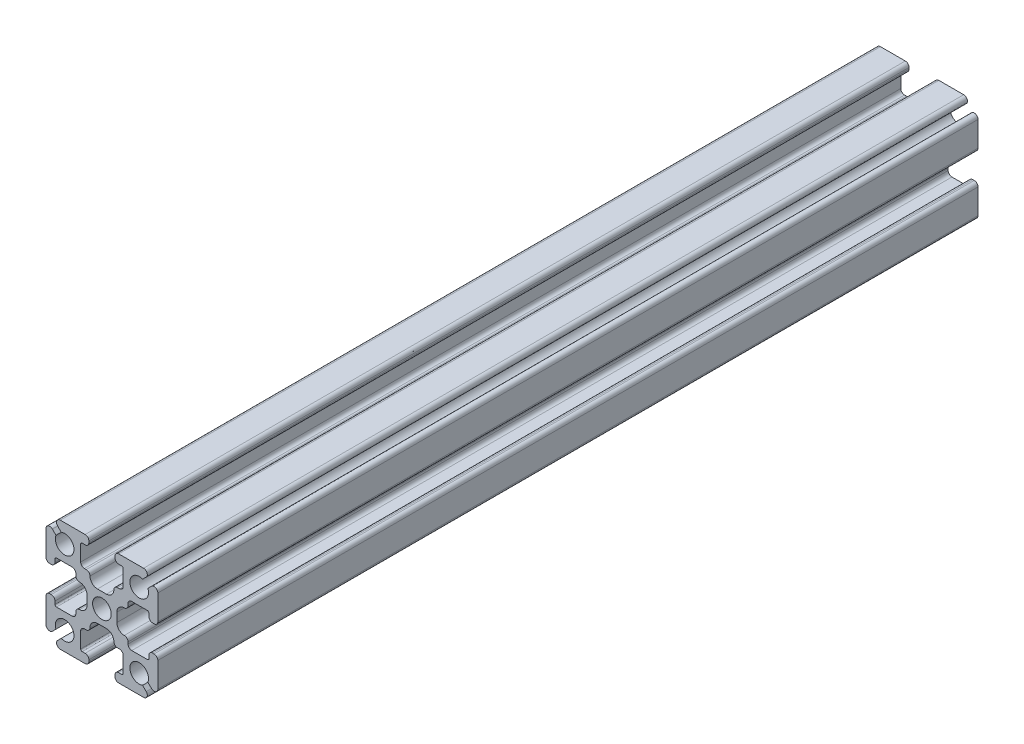
SolidWorks part; units mm, degrees
ref_plane "Front" through (0, 0, 0) normal (0, 0, 1) x (1, 0, 0)
ref_plane "Top" through (0, 0, 0) normal (0, 1, 0) x (1, 0, 0)
ref_plane "Right" through (0, 0, 0) normal (1, 0, 0) x (0, 0, -1)
sketch "Sketch1" plane through (0, 0, 0) normal (0, 0, 1) x (1, 0, 0)
  line L0 (6.6464, 5.9393) -> (6.1636, 5.4565)
  line L1 (5.4565, 6.1636) -> (5.9393, 6.6464)
  line L2 (5.5858, 7.5) -> (2.25, 7.5)
  line L3 (1.75, 7) -> (1.75, 6.8)
  line L4 (2.25, 6.3) -> (2.65, 6.3)
  line L5 (2.85, 6.1) -> (2.85, 4)
  line L6 (2.35, 3.5) -> (2.1, 3.5)
  line L7 (0.6, 2) -> (-0.6, 2)
  line L8 (-2.1, 3.5) -> (-2.35, 3.5)
  line L9 (-2.85, 4) -> (-2.85, 6.1)
  line L10 (-2.65, 6.3) -> (-2.25, 6.3)
  line L11 (-1.75, 6.8) -> (-1.75, 7)
  line L12 (-2.25, 7.5) -> (-5.5858, 7.5)
  line L13 (-5.9393, 6.6464) -> (-5.4565, 6.1636)
  line L14 (-6.1636, 5.4565) -> (-6.6464, 5.9393)
  line L15 (-7.5, 5.5858) -> (-7.5, 2.25)
  line L16 (-7, 1.75) -> (-6.8, 1.75)
  line L17 (-6.3, 2.25) -> (-6.3, 2.65)
  line L18 (-6.1, 2.85) -> (-4, 2.85)
  line L19 (-3.5, 2.35) -> (-3.5, 2.1)
  line L20 (-2, 0.6) -> (-2, -0.6)
  line L21 (-3.5, -2.1) -> (-3.5, -2.35)
  line L22 (-4, -2.85) -> (-6.1, -2.85)
  line L23 (-6.3, -2.65) -> (-6.3, -2.25)
  line L24 (-6.8, -1.75) -> (-7, -1.75)
  line L25 (-7.5, -2.25) -> (-7.5, -5.5858)
  line L26 (-6.6464, -5.9393) -> (-6.1636, -5.4565)
  line L27 (-5.4565, -6.1636) -> (-5.9393, -6.6464)
  line L28 (-5.5858, -7.5) -> (-2.25, -7.5)
  line L29 (-1.75, -7) -> (-1.75, -6.8)
  line L30 (-2.25, -6.3) -> (-2.65, -6.3)
  line L31 (-2.85, -6.1) -> (-2.85, -4)
  line L32 (-2.35, -3.5) -> (-2.1, -3.5)
  line L33 (-0.6, -2) -> (0.6, -2)
  line L34 (2.1, -3.5) -> (2.35, -3.5)
  line L35 (2.85, -4) -> (2.85, -6.1)
  line L36 (2.65, -6.3) -> (2.25, -6.3)
  line L37 (1.75, -6.8) -> (1.75, -7)
  line L38 (2.25, -7.5) -> (5.5858, -7.5)
  line L39 (5.9393, -6.6464) -> (5.4565, -6.1636)
  line L40 (6.1636, -5.4565) -> (6.6464, -5.9393)
  line L41 (7.5, -5.5858) -> (7.5, -2.25)
  line L42 (7, -1.75) -> (6.8, -1.75)
  line L43 (6.3, -2.25) -> (6.3, -2.65)
  line L44 (6.1, -2.85) -> (4, -2.85)
  line L45 (3.5, -2.35) -> (3.5, -2.1)
  line L46 (2, -0.6) -> (2, 0.6)
  line L47 (3.5, 2.1) -> (3.5, 2.35)
  line L48 (4, 2.85) -> (6.1, 2.85)
  line L49 (6.3, 2.65) -> (6.3, 2.25)
  line L50 (6.8, 1.75) -> (7, 1.75)
  line L51 (7.5, 2.25) -> (7.5, 5.5858)
  circle A0 centre (0, 0) radius 1.25
  arc A1 (6.1636, 5.4565) -> (5.4565, 6.1636) centre (5, 5) cw
  arc A2 (5.9393, 6.6464) -> (5.5858, 7.5) centre (5.5858, 7) ccw
  arc A3 (2.25, 7.5) -> (1.75, 7) centre (2.25, 7) ccw
  arc A4 (1.75, 6.8) -> (2.25, 6.3) centre (2.25, 6.8) ccw
  arc A5 (2.65, 6.3) -> (2.85, 6.1) centre (2.65, 6.1) cw
  arc A6 (2.85, 4) -> (2.35, 3.5) centre (2.35, 4) cw
  arc A7 (2.1, 3.5) -> (1.6, 3) centre (2.1, 3) ccw
  arc A8 (1.6, 3) -> (0.6, 2) centre (0.6, 3) cw
  arc A9 (-0.6, 2) -> (-1.6, 3) centre (-0.6, 3) cw
  arc A10 (-1.6, 3) -> (-2.1, 3.5) centre (-2.1, 3) ccw
  arc A11 (-2.35, 3.5) -> (-2.85, 4) centre (-2.35, 4) cw
  arc A12 (-2.85, 6.1) -> (-2.65, 6.3) centre (-2.65, 6.1) cw
  arc A13 (-2.25, 6.3) -> (-1.75, 6.8) centre (-2.25, 6.8) ccw
  arc A14 (-1.75, 7) -> (-2.25, 7.5) centre (-2.25, 7) ccw
  arc A15 (-5.5858, 7.5) -> (-5.9393, 6.6464) centre (-5.5858, 7) ccw
  arc A16 (-5.4565, 6.1636) -> (-6.1636, 5.4565) centre (-5, 5) cw
  arc A17 (-6.6464, 5.9393) -> (-7.5, 5.5858) centre (-7, 5.5858) ccw
  arc A18 (-7.5, 2.25) -> (-7, 1.75) centre (-7, 2.25) ccw
  arc A19 (-6.8, 1.75) -> (-6.3, 2.25) centre (-6.8, 2.25) ccw
  arc A20 (-6.3, 2.65) -> (-6.1, 2.85) centre (-6.1, 2.65) cw
  arc A21 (-4, 2.85) -> (-3.5, 2.35) centre (-4, 2.35) cw
  arc A22 (-3.5, 2.1) -> (-3, 1.6) centre (-3, 2.1) ccw
  arc A23 (-3, 1.6) -> (-2, 0.6) centre (-3, 0.6) cw
  arc A24 (-2, -0.6) -> (-3, -1.6) centre (-3, -0.6) cw
  arc A25 (-3, -1.6) -> (-3.5, -2.1) centre (-3, -2.1) ccw
  arc A26 (-3.5, -2.35) -> (-4, -2.85) centre (-4, -2.35) cw
  arc A27 (-6.1, -2.85) -> (-6.3, -2.65) centre (-6.1, -2.65) cw
  arc A28 (-6.3, -2.25) -> (-6.8, -1.75) centre (-6.8, -2.25) ccw
  arc A29 (-7, -1.75) -> (-7.5, -2.25) centre (-7, -2.25) ccw
  arc A30 (-7.5, -5.5858) -> (-6.6464, -5.9393) centre (-7, -5.5858) ccw
  arc A31 (-6.1636, -5.4565) -> (-5.4565, -6.1636) centre (-5, -5) cw
  arc A32 (-5.9393, -6.6464) -> (-5.5858, -7.5) centre (-5.5858, -7) ccw
  arc A33 (-2.25, -7.5) -> (-1.75, -7) centre (-2.25, -7) ccw
  arc A34 (-1.75, -6.8) -> (-2.25, -6.3) centre (-2.25, -6.8) ccw
  arc A35 (-2.65, -6.3) -> (-2.85, -6.1) centre (-2.65, -6.1) cw
  arc A36 (-2.85, -4) -> (-2.35, -3.5) centre (-2.35, -4) cw
  arc A37 (-2.1, -3.5) -> (-1.6, -3) centre (-2.1, -3) ccw
  arc A38 (-1.6, -3) -> (-0.6, -2) centre (-0.6, -3) cw
  arc A39 (0.6, -2) -> (1.6, -3) centre (0.6, -3) cw
  arc A40 (1.6, -3) -> (2.1, -3.5) centre (2.1, -3) ccw
  arc A41 (2.35, -3.5) -> (2.85, -4) centre (2.35, -4) cw
  arc A42 (2.85, -6.1) -> (2.65, -6.3) centre (2.65, -6.1) cw
  arc A43 (2.25, -6.3) -> (1.75, -6.8) centre (2.25, -6.8) ccw
  arc A44 (1.75, -7) -> (2.25, -7.5) centre (2.25, -7) ccw
  arc A45 (5.5858, -7.5) -> (5.9393, -6.6464) centre (5.5858, -7) ccw
  arc A46 (5.4565, -6.1636) -> (6.1636, -5.4565) centre (5, -5) cw
  arc A47 (6.6464, -5.9393) -> (7.5, -5.5858) centre (7, -5.5858) ccw
  arc A48 (7.5, -2.25) -> (7, -1.75) centre (7, -2.25) ccw
  arc A49 (6.8, -1.75) -> (6.3, -2.25) centre (6.8, -2.25) ccw
  arc A50 (6.3, -2.65) -> (6.1, -2.85) centre (6.1, -2.65) cw
  arc A51 (4, -2.85) -> (3.5, -2.35) centre (4, -2.35) cw
  arc A52 (3.5, -2.1) -> (3, -1.6) centre (3, -2.1) ccw
  arc A53 (3, -1.6) -> (2, -0.6) centre (3, -0.6) cw
  arc A54 (2, 0.6) -> (3, 1.6) centre (3, 0.6) cw
  arc A55 (3, 1.6) -> (3.5, 2.1) centre (3, 2.1) ccw
  arc A56 (3.5, 2.35) -> (4, 2.85) centre (4, 2.35) cw
  arc A57 (6.1, 2.85) -> (6.3, 2.65) centre (6.1, 2.65) cw
  arc A58 (6.3, 2.25) -> (6.8, 1.75) centre (6.8, 2.25) ccw
  arc A59 (7, 1.75) -> (7.5, 2.25) centre (7, 2.25) ccw
  arc A60 (7.5, 5.5858) -> (6.6464, 5.9393) centre (7, 5.5858) ccw
extrude "Boss-Extrude1" add sketch "Sketch1" along normal blind 110
